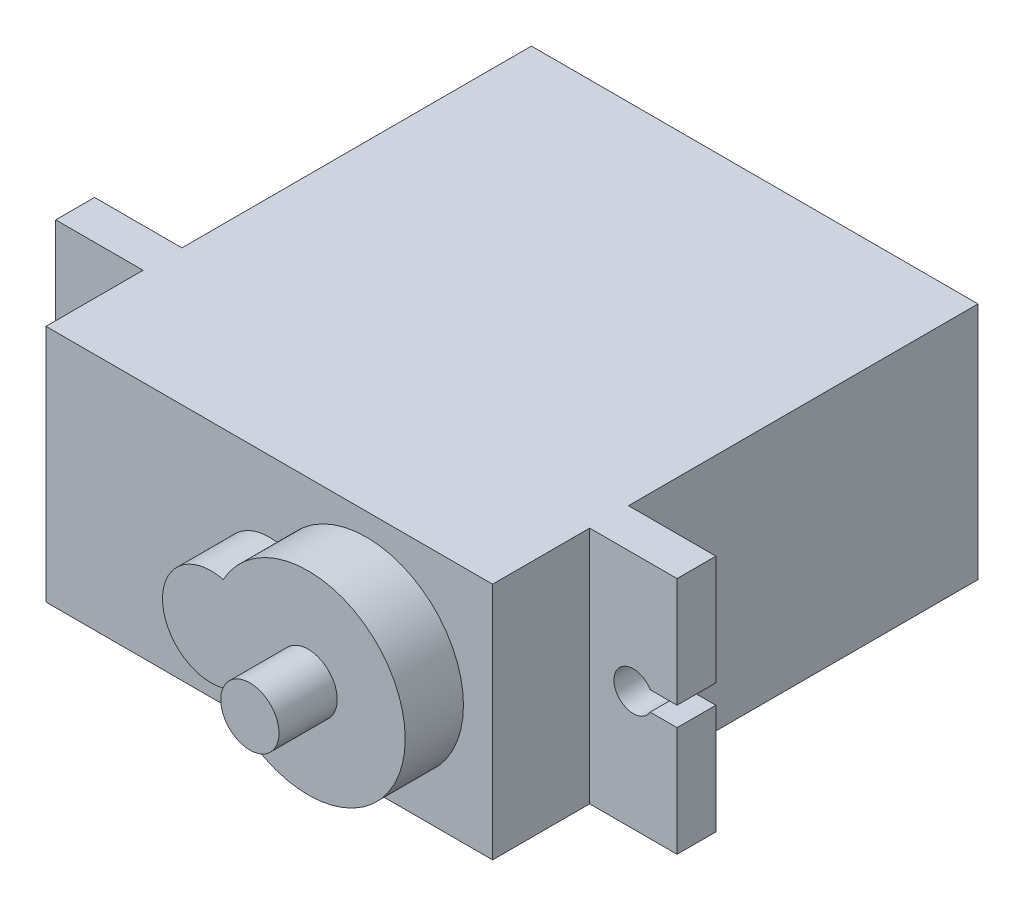
SolidWorks part; units mm, degrees
ref_plane "前视基准面" through (0, 0, 0) normal (0, 0, 1) x (1, 0, 0)
ref_plane "上视基准面" through (0, 0, 0) normal (0, 1, 0) x (1, 0, 0)
ref_plane "右视基准面" through (0, 0, 0) normal (1, 0, 0) x (0, 0, -1)
sketch "草图1" plane through (0, 0, 0) normal (0, 0, 1) x (1, 0, 0)
  line L1 (-11.5, -6.15) -> (11.5, -6.15)
  line L2 (-11.5, -6.15) -> (-11.5, 6.15)
  line L3 (-11.5, 6.15) -> (11.5, 6.15)
  line L4 (11.5, -6.15) -> (11.5, 6.15)
  line L5 (-11.5, -6.15) -> (11.5, 6.15) construction
  line L6 (-11.5, 6.15) -> (11.5, -6.15) construction
  point P0 (0, 0)
  dimension "D1" = 23
  dimension "D2" = 12.3
extrude "凸台-拉伸1" add sketch "草图1" along normal blind 25
sketch "草图3" plane through (0, 0, 25) normal (0, 0, 1) x (1, 0, 0)
  line L0 (0, 0) -> (5, 0) construction
  circle A0 centre (5, 0) radius 5
  circle A1 centre (0, 0) radius 2.5
  dimension "D1" = 10
  dimension "D2" = 5
  dimension "D3" = 5
extrude "凸台-拉伸2" add sketch "草图3" along normal blind 3
sketch "草图4" plane through (0, 0, 28) normal (0, 0, 1) x (1, 0, 0)
  circle A0 centre (5, 0) radius 1.5
  dimension "D1" = 3
extrude "凸台-拉伸3" add sketch "草图4" along normal blind 3
sketch "草图5" plane through (0, 0, 25) normal (0, 0, 1) x (1, 0, 0)
  line L1 (-11.5, 6.15) -> (-16, 6.15)
  line L2 (-11.5, 6.15) -> (-11.5, -6.15)
  line L3 (-11.5, -6.15) -> (-16, -6.15)
  line L4 (-16, 6.15) -> (-16, -6.15)
  line L5 (11.5, -6.15) -> (16, -6.15)
  line L6 (11.5, -6.15) -> (11.5, 6.15)
  line L7 (11.5, 6.15) -> (16, 6.15)
  line L8 (16, -6.15) -> (16, 6.15)
  dimension "D1" = 4.5
  dimension "D2" = 4.5
extrude "凸台-拉伸4" add sketch "草图5" against normal blind 2 from offset 5 offset against normal yes
sketch "草图6" plane through (0, 0, 20) normal (0, 0, 1) x (1, 0, 0)
  line L0 (0, 0) -> (-16, 0) construction
  line L1 (-16, 6.15) -> (-16, -6.15) construction
  line L2 (-13.75, 0) -> (-13.75, -6.15) construction
  line L3 (-16, -6.15) -> (-11.5, -6.15) construction
  line L4 (0, 6.15) -> (0, -6.15) construction
  line L5 (11.5, 6.15) -> (-11.5, 6.15) construction
  line L6 (-11.5, -6.15) -> (11.5, -6.15) construction
  circle A0 centre (-13.75, 0) radius 1
  circle A1 centre (13.75, 0) radius 1
  dimension "D1" = 2
extrude "切除-拉伸1" cut sketch "草图6" against normal blind 3
sketch "草图7" plane through (0, 0, 20) normal (0, 0, 1) x (1, 0, 0)
  line L0 (-16, 0) -> (-11.5, 0) construction
  line L1 (-16, 6.15) -> (-16, -6.15) construction
  line L2 (-11.5, 6.15) -> (-11.5, -6.15) construction
  line L3 (-16, 0.5) -> (-14.616, 0.5)
  line L4 (-14.616, 0.5) -> (-14.616, -0.5)
  line L5 (-14.616, -0.5) -> (-16, -0.5)
  line L6 (-16, -0.5) -> (-16, 0.5)
  line L7 (0, 6.15) -> (0, -6.15) construction
  line L8 (11.5, 6.15) -> (-11.5, 6.15) construction
  line L9 (-11.5, -6.15) -> (11.5, -6.15) construction
  line L10 (16, -0.5) -> (16, 0.5)
  line L11 (14.616, -0.5) -> (16, -0.5)
  line L12 (14.616, 0.5) -> (14.616, -0.5)
  line L13 (16, 0.5) -> (14.616, 0.5)
  circle A0 centre (-13.75, 0) radius 1 construction
  dimension "D1" = 1
extrude "切除-拉伸2" cut sketch "草图7" against normal blind 10
